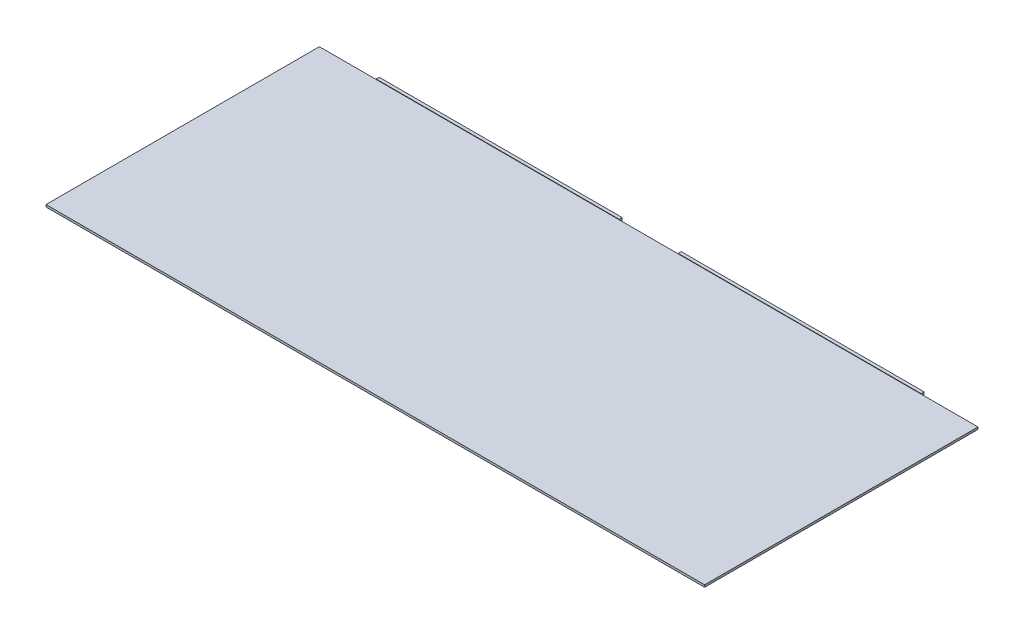
SolidWorks part; units mm, degrees
material "6061-T6 (SS)"
ref_plane "X-Y Datum" through (0, 0, 0) normal (0, 0, 1) x (1, 0, 0)
ref_plane "X-Z Datum" through (0, 0, 0) normal (0, 1, 0) x (1, 0, 0)
ref_plane "Y-Z Datum" through (0, 0, 0) normal (1, 0, 0) x (0, 0, -1)
sketch "Sketch1" plane through (0, 0, 0) normal (0, 1, 0) x (1, 0, 0)
  line L1 (-344.2208, 142.875) -> (344.2208, 142.875)
  line L2 (-344.2208, 142.875) -> (-344.2208, -142.875)
  line L3 (-344.2208, -142.875) -> (344.2208, -142.875)
  line L4 (344.2208, 142.875) -> (344.2208, -142.875)
  line L5 (-344.2208, 142.875) -> (344.2208, -142.875) construction
  line L6 (-344.2208, -142.875) -> (344.2208, 142.875) construction
  point P0 (0, 0)
  dimension "D1" = 688.4416
  dimension "D2" = 285.75
extrude "Boss-Extrude1" add sketch "Sketch1" along normal mid plane 2.286
sketch "Sketch2" plane through (0, 0, -142.875) normal (0, 0, -1) x (-1, 0, 0)
  line L20 (-344.2208, -1.143) -> (344.2208, -1.143) construction
  line L21 (-284.8229, -1.143) -> (-30.8229, -1.143)
  line L22 (30.8229, -1.143) -> (284.8229, -1.143)
  line L40 (30.8229, -1.143) -> (30.8229, 1.5875)
  line L41 (30.8229, 1.5875) -> (284.8229, 1.5875)
  line L42 (284.8229, 1.5875) -> (284.8229, -1.143)
  line L56 (-284.8229, -1.143) -> (-284.8229, 1.5875)
  line L57 (-284.8229, 1.5875) -> (-30.8229, 1.5875)
  line L58 (-30.8229, 1.5875) -> (-30.8229, -1.143)
extrude "Boss-Extrude2" add sketch "Sketch2" along normal blind 3.175
